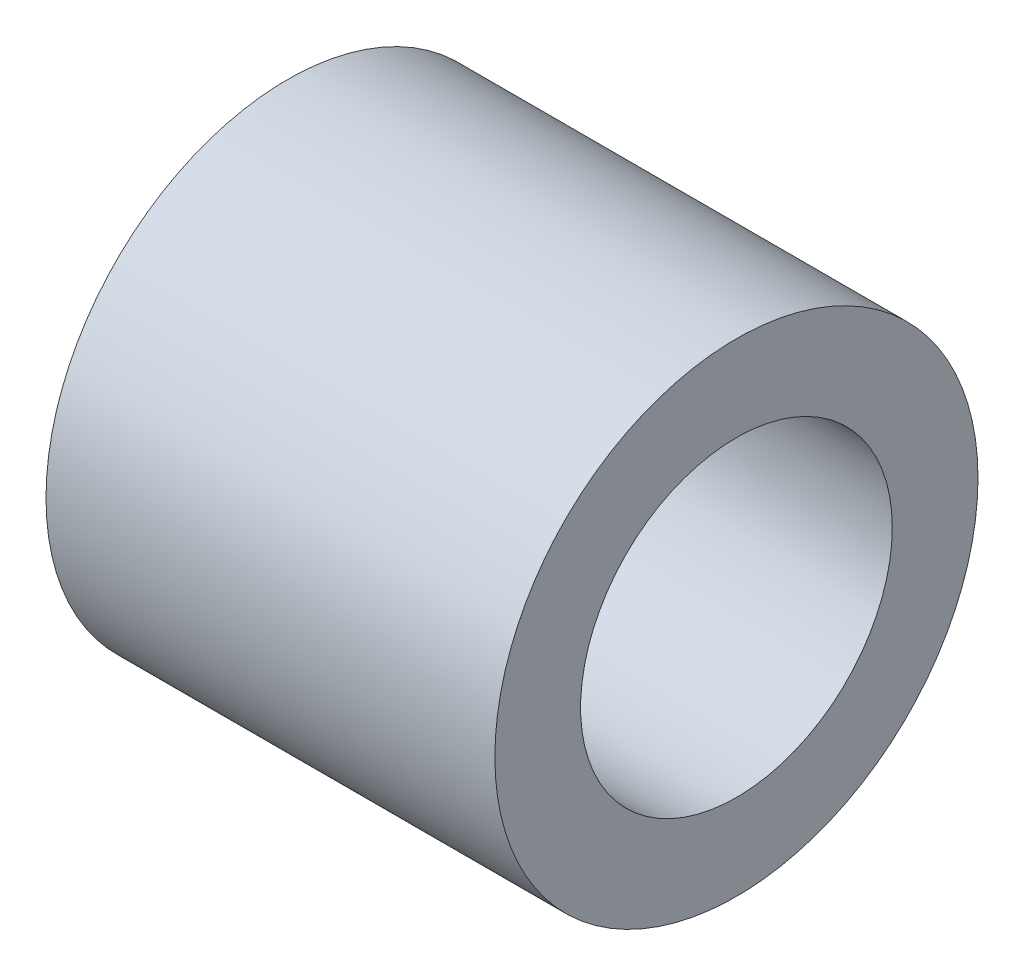
SolidWorks part; units mm, degrees
material "Brass"
ref_plane "Front" through (0, 0, 0) normal (0, 0, 1) x (1, 0, 0)
ref_plane "Top" through (0, 0, 0) normal (0, 1, 0) x (1, 0, 0)
ref_plane "Right" through (0, 0, 0) normal (1, 0, 0) x (0, 0, -1)
sketch "Sketch1" plane through (0, 0, 0) normal (1, 0, 0) x (0, 0, -1)
  circle A0 centre (0, 0) radius 7.75
  circle A1 centre (0, 0) radius 5
  dimension "D1" = 10
  dimension "D2" = 15.5
extrude "Boss-Extrude1" add sketch "Sketch1" along normal mid plane 14.4
